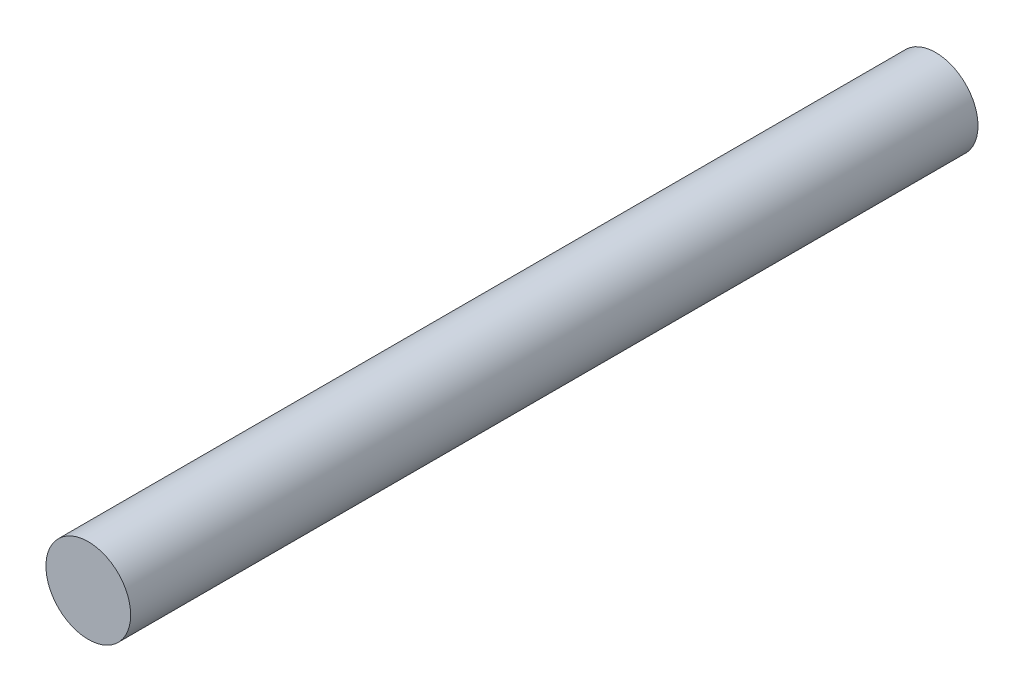
SolidWorks part; units mm, degrees
ref_plane "Plan de face" through (0, 0, 0) normal (0, 0, 1) x (1, 0, 0)
ref_plane "Plan de dessus" through (0, 0, 0) normal (0, 1, 0) x (1, 0, 0)
ref_plane "Plan de droite" through (0, 0, 0) normal (1, 0, 0) x (0, 0, -1)
sketch "Esquisse1" plane through (0, 0, 0) normal (0, 0, 1) x (1, 0, 0)
  circle A0 centre (0, 0) radius 10
  dimension "D1" = 20
extrude "Boss.-Extru.1" add sketch "Esquisse1" along normal blind 200
